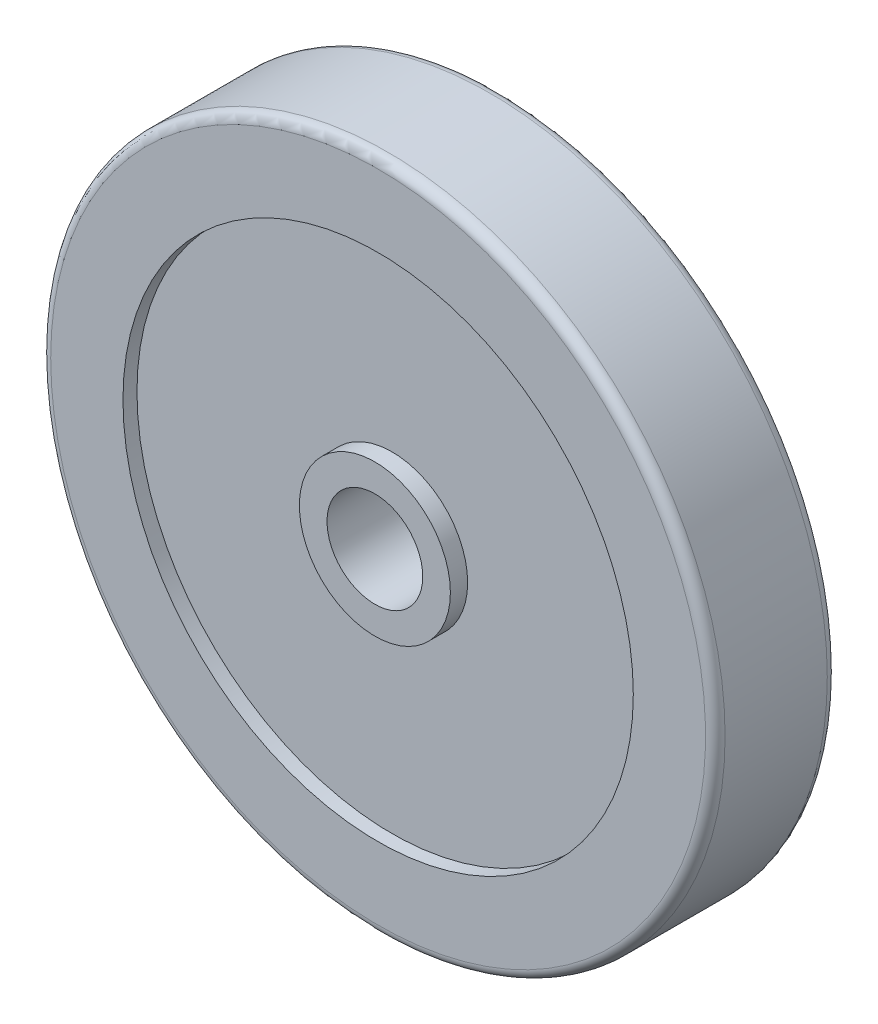
SolidWorks part; units mm, degrees
material "Plain Carbon Steel"
ref_plane "Front Plane" through (0, 0, 0) normal (0, 0, 1) x (1, 0, 0)
ref_plane "Top Plane" through (0, 0, 0) normal (0, 1, 0) x (1, 0, 0)
ref_plane "Right Plane" through (0, 0, 0) normal (1, 0, 0) x (0, 0, -1)
sketch "Sketch1" plane through (0, 0, 0) normal (1, 0, 0) x (0, 0, -1)
  line L0 (-15.3879, 0) -> (0, 0) construction
  line L1 (0, 0) -> (0, 14.7) construction
  line L2 (19.7, 14.7) -> (-19.7, 14.7)
  line L3 (-19.7, 14.7) -> (-19.7, 23.2)
  line L4 (-19.7, 23.2) -> (-14.4, 23.2)
  line L5 (-14.4, 23.2) -> (-14.4, 78.4)
  line L6 (-14.4, 78.4) -> (-18.7, 78.4)
  line L7 (-18.7, 78.4) -> (-18.7, 103.6)
  line L8 (-18.7, 103.6) -> (18.7, 103.6)
  line L9 (18.7, 78.4) -> (18.7, 103.6)
  line L10 (14.4, 78.4) -> (18.7, 78.4)
  line L11 (14.4, 23.2) -> (14.4, 78.4)
  line L12 (19.7, 23.2) -> (14.4, 23.2)
  line L13 (19.7, 14.7) -> (19.7, 23.2)
  line L14 (-7.5, 98.8595) -> (-7.5, 22.8943)
  line L15 (-7.5, 98.8595) -> (7.5, 98.8595)
  line L16 (-7.5, 22.8943) -> (7.5, 22.8943)
  line L17 (7.5, 98.8595) -> (7.5, 22.8943)
  line L18 (-7.5, 98.8595) -> (7.5, 22.8943) construction
  line L19 (-7.5, 22.8943) -> (7.5, 98.8595) construction
  point P12 (0, 103.6)
  point P18 (0, 60.8769)
  dimension "D1" = 8.5
  dimension "D2" = 55.2
  dimension "D3" = 25.2
  dimension "D4" = 37.4
  dimension "D5" = 4.3
  dimension "D6" = 5.3
  dimension "D7" = 29.4
  dimension "D8" = 15
revolve "Revolve1" add sketch "Sketch1" angle 360 about L0
fillet "Fillet1" radius 3 2 edges at (103.6, 0, -18.7) (103.6, 0, 18.7)
